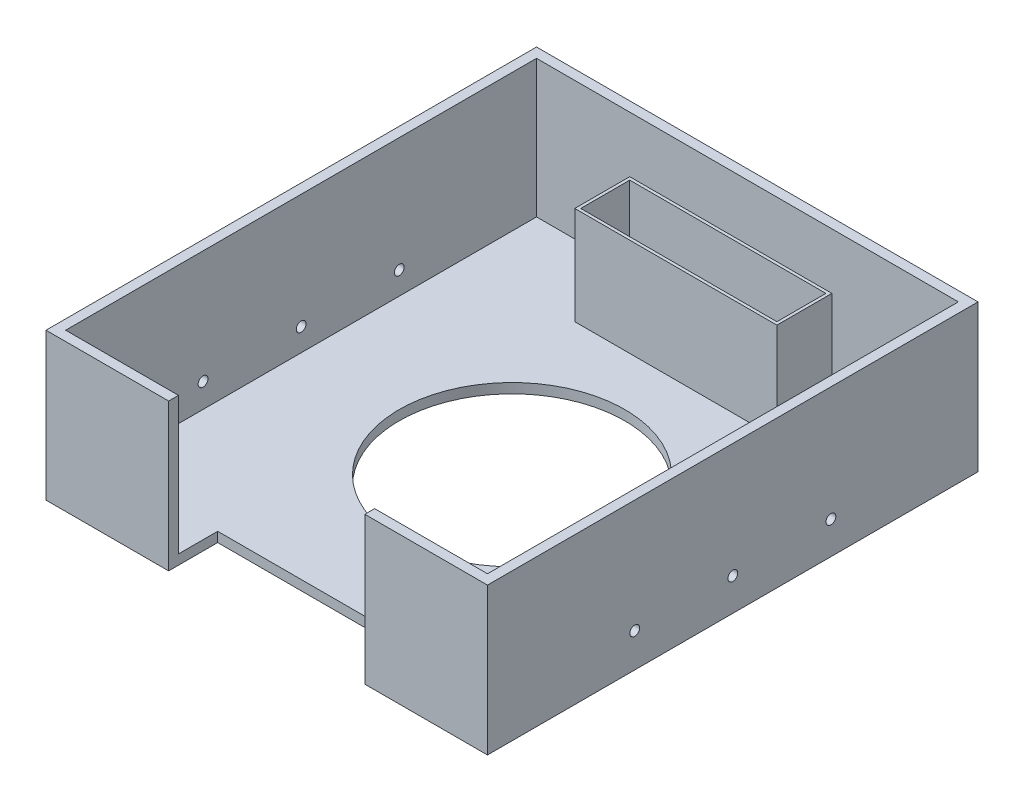
SolidWorks part; units mm, degrees
ref_plane "Front Plane" through (0, 0, 0) normal (0, 0, 1) x (1, 0, 0)
ref_plane "Top Plane" through (0, 0, 0) normal (0, 1, 0) x (1, 0, 0)
ref_plane "Right Plane" through (0, 0, 0) normal (1, 0, 0) x (0, 0, -1)
sketch "Sketch1" plane through (0, 0, 0) normal (0, 1, 0) x (1, 0, 0)
  line L0 (-225, 250) -> (225, 250)
  line L1 (-225, -250) -> (225, -250)
  line L2 (-225, -250) -> (-225, 250)
  line L4 (225, -250) -> (225, 250)
  point P0 (0, 0)
  dimension "D2" = 450
  dimension "D3" = 225
  dimension "D4" = 500
  dimension "D5" = 500
  dimension "D6" = 250
extrude "Boss-Extrude1" add sketch "Sketch1" along normal blind 10
sketch "Sketch2" plane through (0, 10, 0) normal (0, 1, 0) x (1, 0, 0)
  line L4 (215, -240) -> (215, 240)
  line L5 (215, 240) -> (-215, 240)
  line L6 (-215, 240) -> (-215, -240)
  line L7 (-215, -240) -> (215, -240)
  line L8 (225, -250) -> (225, 250)
  line L12 (225, 250) -> (-225, 250)
  line L18 (-225, 250) -> (-225, -250)
  line L19 (-225, -250) -> (225, -250)
  line L20 (225, -250) -> (225, 250)
  line L21 (225, 250) -> (-225, 250)
  line L22 (-225, 250) -> (-225, -250)
  line L23 (-225, -250) -> (225, -250)
  dimension "D1" = 0
  dimension "D2" = 10
extrude "Boss-Extrude2" add sketch "Sketch2" along normal blind 140
sketch "Sketch3" plane through (0, 10, 0) normal (0, 1, 0) x (1, 0, 0)
  circle A0 centre (0, 0) radius 115
extrude "Cut-Extrude1" cut sketch "Sketch3" against normal blind 10
sketch "Sketch5" plane through (0, 150, 0) normal (0, 1, 0) x (1, 0, 0)
  line L0 (-225, -250) -> (225, -250) construction
  line L1 (-100, -300) -> (100, -300)
  line L2 (-100, -300) -> (-100, -200)
  line L3 (-100, -200) -> (100, -200)
  line L4 (100, -300) -> (100, -200)
  line L5 (-100, -300) -> (100, -200) construction
  line L6 (-100, -200) -> (100, -300) construction
  point P0 (0, -250)
  dimension "D1" = 200
  dimension "D2" = 100
  dimension "D3" = 250
extrude "Cut-Extrude3" cut sketch "Sketch5" against normal through all
sketch "Sketch6" plane through (225, 0, 0) normal (1, 0, 0) x (0, 0, -1)
  line L2 (-250, 0) -> (250, 0) construction
  line L3 (-250, 150) -> (-250, 0) construction
  circle A0 centre (-99.9, 34.7) radius 5
  circle A1 centre (0.1, 33.13) radius 5
  circle A2 centre (100.1, 33.13) radius 5
  dimension "D5" = 100
  dimension "D1" = 150.1
  dimension "D2" = 33.13
  dimension "D3" = 33.13
  dimension "D4" = 100
  dimension "D6" = 34.7
extrude "Cut-Extrude4" cut sketch "Sketch6" against normal blind 10
sketch "Sketch7" plane through (-225, 0, 0) normal (-1, 0, 0) x (0, 0, 1)
  circle A12 centre (-100.1, 33.13) radius 5
  circle A13 centre (-0.1, 33.13) radius 5
  circle A14 centre (99.9, 34.7) radius 5
extrude "Cut-Extrude5" cut sketch "Sketch7" against normal blind 10
sketch "Sketch8" plane through (0, 10, 0) normal (0, 1, 0) x (1, 0, 0)
  line L0 (225, 250) -> (-225, 250) construction
  line L1 (-100, 220) -> (100, 220)
  line L2 (-100, 220) -> (-100, 170)
  line L3 (-100, 170) -> (100, 170)
  line L4 (100, 220) -> (100, 170)
  line L5 (-215, 240) -> (-215, -240) construction
  line L6 (215, -240) -> (215, 240) construction
  line L7 (-103, 223) -> (103, 223)
  line L8 (103, 223) -> (103, 167)
  line L9 (-103, 167) -> (103, 167)
  line L10 (-103, 223) -> (-103, 167)
  dimension "D1" = 30
  dimension "D2" = 50
  dimension "D3" = 50
  dimension "D4" = 200
  dimension "D5" = 115
  dimension "D6" = 115
  dimension "D7" = 3
extrude "Boss-Extrude3" add sketch "Sketch8" along normal blind 100
